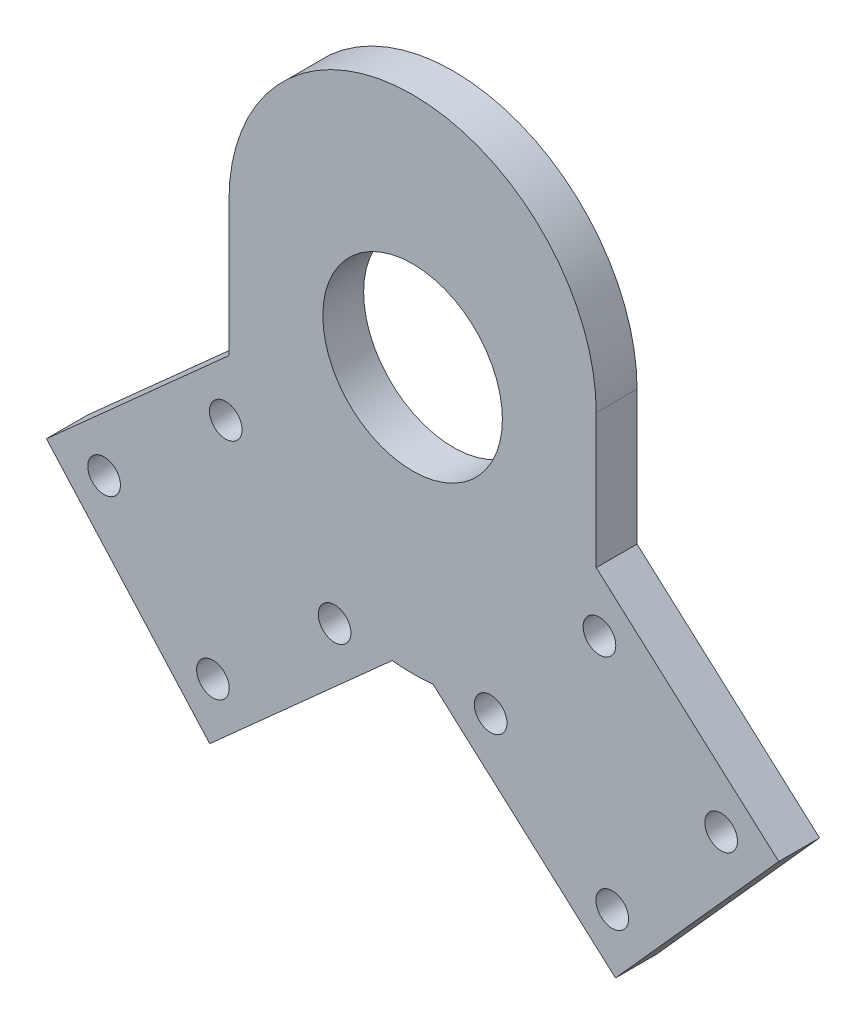
SolidWorks part; units mm, degrees
ref_plane "Front Plane" through (0, 0, 0) normal (0, 0, 1) x (1, 0, 0)
ref_plane "Top Plane" through (0, 0, 0) normal (0, 1, 0) x (1, 0, 0)
ref_plane "Right Plane" through (0, 0, 0) normal (1, 0, 0) x (0, 0, -1)
sketch "Sketch2" plane through (0, 0, 0) normal (0, 0, 1) x (1, 0, 0)
  line L0 (-22.5, 0) -> (-2.5, -22.3607)
  line L1 (-22.5, 0) -> (-44.8607, -20)
  line L2 (-2.5, -22.3607) -> (-24.8607, -42.3607)
  line L3 (-44.8607, -20) -> (-24.8607, -42.3607)
  line L4 (2.5, -22.3607) -> (22.5, 0)
  line L5 (2.5, -22.3607) -> (24.8607, -42.3607)
  line L6 (22.5, 0) -> (44.8607, -20)
  line L7 (24.8607, -42.3607) -> (44.8607, -20)
  line L8 (-22.5, 0) -> (0, 0)
  line L9 (0, 0) -> (-2.5, -22.3607)
  line L10 (2.5, -22.3607) -> (0, 0)
  line L11 (22.5, 0) -> (0, 0)
  line L12 (-22.5, 0) -> (-22.5, 16.444)
  line L14 (22.5, 16.444) -> (22.5, 0)
  line L15 (-22.5, 16.444) -> (22.5, 16.444)
  line L16 (-22.5, 16.444) -> (-22.5, 0)
  line L17 (-22.5, 0) -> (22.5, 0)
  line L18 (22.5, 16.444) -> (22.5, 0)
  circle A0 centre (0, 0) radius 22.5
  circle A2 centre (0, 16.444) radius 22.5
  dimension "D5" = 45
  dimension "D1" = 30
  dimension "D2" = 30
  dimension "D3" = 30
  dimension "D4" = 30
extrude "Boss-Extrude1" add sketch "Sketch2" along normal blind 5 contours L0 L1 L3 L2 | L4 L5 L7 L6 | A0 | A2 | L16 L15 L18 L17
sketch "Sketch3" plane through (0, 0, 0) normal (0, 0, -1) x (-1, 0, 0)
  line L0 (2.5, -22.3607) -> (24.8607, -42.3607) construction
  line L1 (44.8607, -20) -> (24.8607, -42.3607) construction
  line L2 (-22.5, 0) -> (-44.8607, -20) construction
  line L3 (-24.8607, -42.3607) -> (-44.8607, -20) construction
  line L4 (-22.5, 0) -> (-2.5, -22.3607)
  line L5 (-2.5, -22.3607) -> (-24.8607, -42.3607) construction
  line L6 (-37.8006, -20.3934) -> (-22.8934, -7.0601)
  line L7 (-22.8934, -7.0601) -> (-9.5601, -21.9672)
  line L8 (-9.5601, -21.9672) -> (-24.4672, -35.3006)
  line L9 (-37.8006, -20.3934) -> (-24.4672, -35.3006)
  line L10 (22.5, 0) -> (44.8607, -20) construction
  line L11 (24.4672, -35.3006) -> (37.8006, -20.3934)
  line L12 (37.8006, -20.3934) -> (22.8934, -7.0601)
  line L13 (22.8934, -7.0601) -> (9.5601, -21.9672)
  line L14 (9.5601, -21.9672) -> (24.4672, -35.3006)
  circle A0 centre (-37.8006, -20.3934) radius 2
  circle A1 centre (-22.8934, -7.0601) radius 2
  circle A2 centre (-9.5601, -21.9672) radius 2
  circle A3 centre (-24.4672, -35.3006) radius 2
  circle A4 centre (24.4672, -35.3006) radius 2
  circle A5 centre (37.8006, -20.3934) radius 2
  circle A6 centre (9.5601, -21.9672) radius 2
  circle A7 centre (22.8934, -7.0601) radius 2
  dimension "D3" = 4
  dimension "D7" = 4
  dimension "D8" = 4
  dimension "D9" = 4
  dimension "D12" = 4
  dimension "D15" = 4
  dimension "D16" = 4
  dimension "D17" = 4
  dimension "D1" = 5
  dimension "D2" = 5
  dimension "D4" = 30
  dimension "D5" = 5
  dimension "D6" = 5
  dimension "D10" = 5
  dimension "D11" = 5
  dimension "D13" = 5
  dimension "D14" = 5
extrude "Cut-Extrude1" cut sketch "Sketch3" against normal blind 5 from surface at 0 contours A1 | A0 | A3 | A2 | A6 | A7 | A5 | A4 starting at face at (0, -11.4194, 0)
sketch "Sketch4" plane through (0, 0, 0) normal (0, 0, -1) x (-1, 0, 0)
  line L0 (22.5, 16.444) -> (22.5, 0) construction
  circle A2 centre (0, 10) radius 11
  arc A3 (-2.5, -22.3607) -> (2.5, -22.3607) centre (0, 0) ccw construction
  dimension "D1" = 22.5
  dimension "D3" = 22
  dimension "D2" = 10
extrude "Cut-Extrude2" cut sketch "Sketch4" against normal blind 10
